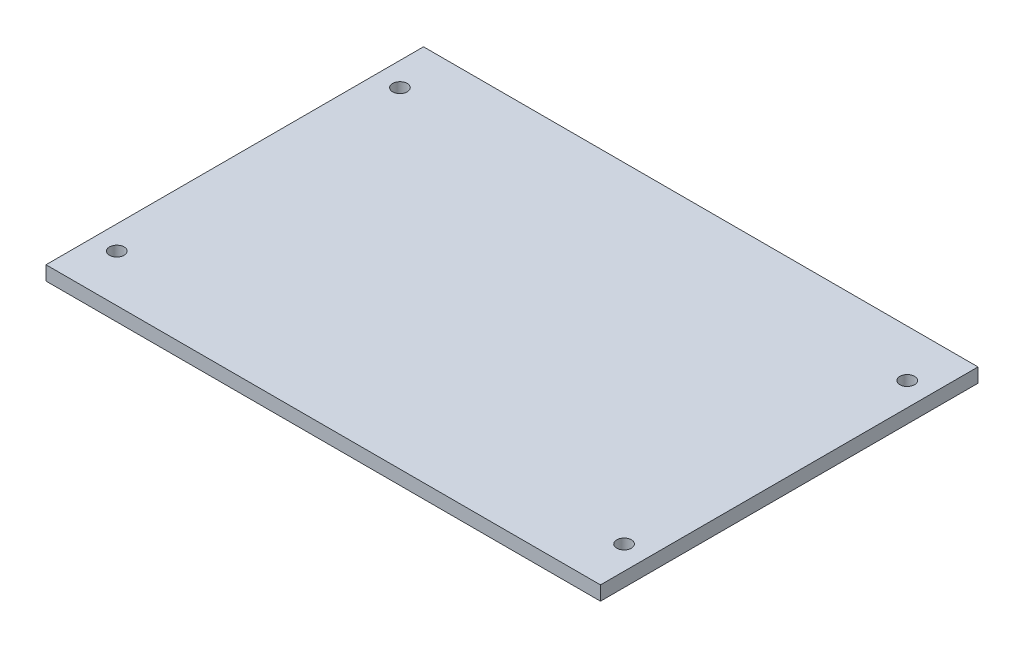
SolidWorks part; units mm, degrees
ref_plane "前视基准面" through (0, 0, 0) normal (0, 0, 1) x (1, 0, 0)
ref_plane "上视基准面" through (0, 0, 0) normal (0, 1, 0) x (1, 0, 0)
ref_plane "右视基准面" through (0, 0, 0) normal (1, 0, 0) x (0, 0, -1)
other "Configuration Table"
sketch "草图1" plane through (0, 0, 0) normal (0, 0, 1) x (1, 0, 0)
  line L10 (0, 0) -> (117.5, 0)
  line L11 (0, 0) -> (0, 3)
  line L12 (0, 3) -> (117.5, 3)
  line L13 (117.5, 0) -> (117.5, 3)
  dimension "D1" = 117.5
  dimension "D2" = 3
extrude "凸台-拉伸1" add sketch "草图1" along normal blind 80
sketch "草图2" plane through (0, 3, 0) normal (0, 1, 0) x (1, 0, 0)
  line L0 (58.75, 0) -> (58.75, -22.575) construction
  line L1 (117.5, 0) -> (0, 0) construction
  line L2 (117.5, -40) -> (147.2193, -40) construction
  line L3 (117.5, -80) -> (117.5, 0) construction
  line L4 (0, -80) -> (0, 0) construction
  circle A0 centre (5, -10) radius 1.55
  circle A1 centre (5, -70) radius 1.55
  circle A2 centre (112.5, -70) radius 1.55
  circle A3 centre (112.5, -10) radius 1.55
  dimension "D3" = 3.1
  dimension "D1" = 5
  dimension "D2" = 30
extrude "切除-拉伸1" cut sketch "草图2" against normal up to next
